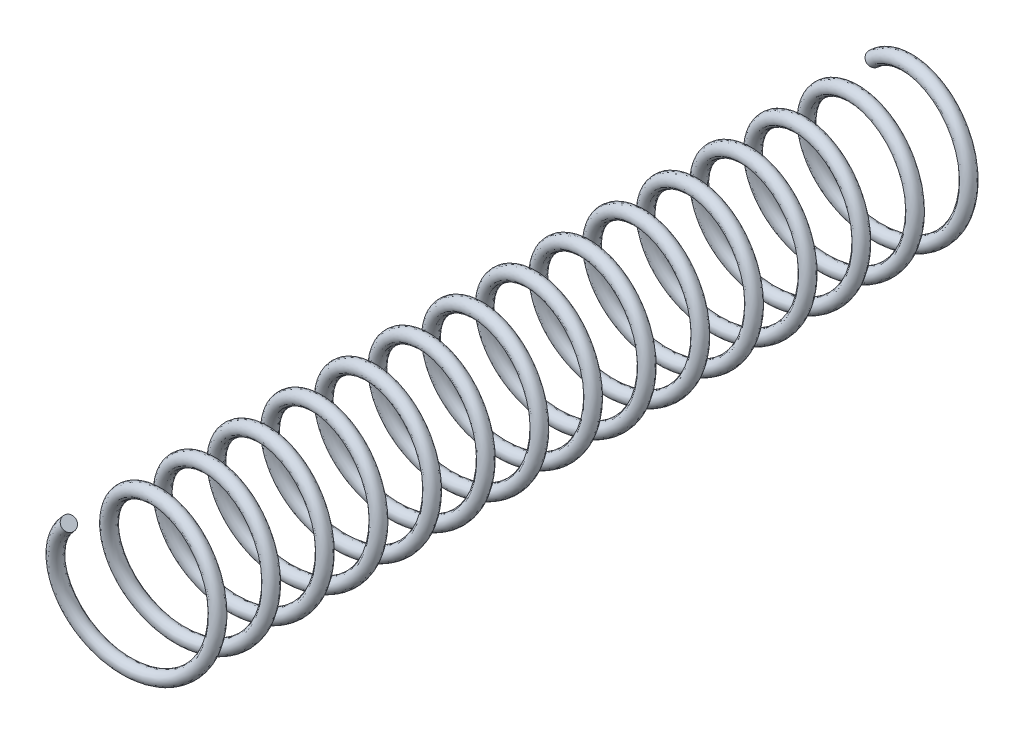
SolidWorks part; units mm, degrees
ref_plane "前视基准面" through (0, 0, 0) normal (0, 0, 1) x (1, 0, 0)
ref_plane "上视基准面" through (0, 0, 0) normal (0, 1, 0) x (1, 0, 0)
ref_plane "右视基准面" through (0, 0, 0) normal (1, 0, 0) x (0, 0, -1)
sketch "草图1" plane through (0, 0, 0) normal (0, 0, 1) x (1, 0, 0)
  circle A0 centre (0, 0) radius 2.5
curve "螺旋线/涡状线1" pitch 2 height 30 turns 15
sweep "扫描1" add path "螺旋线/涡状线1" circular profile diameter 0.5 parameters "D3"=0.5
sketch "草图2" plane through (0, 0, 0) normal (0, 0, 1) x (1, 0, 0)
  circle A0 centre (0, 0) radius 2.5
